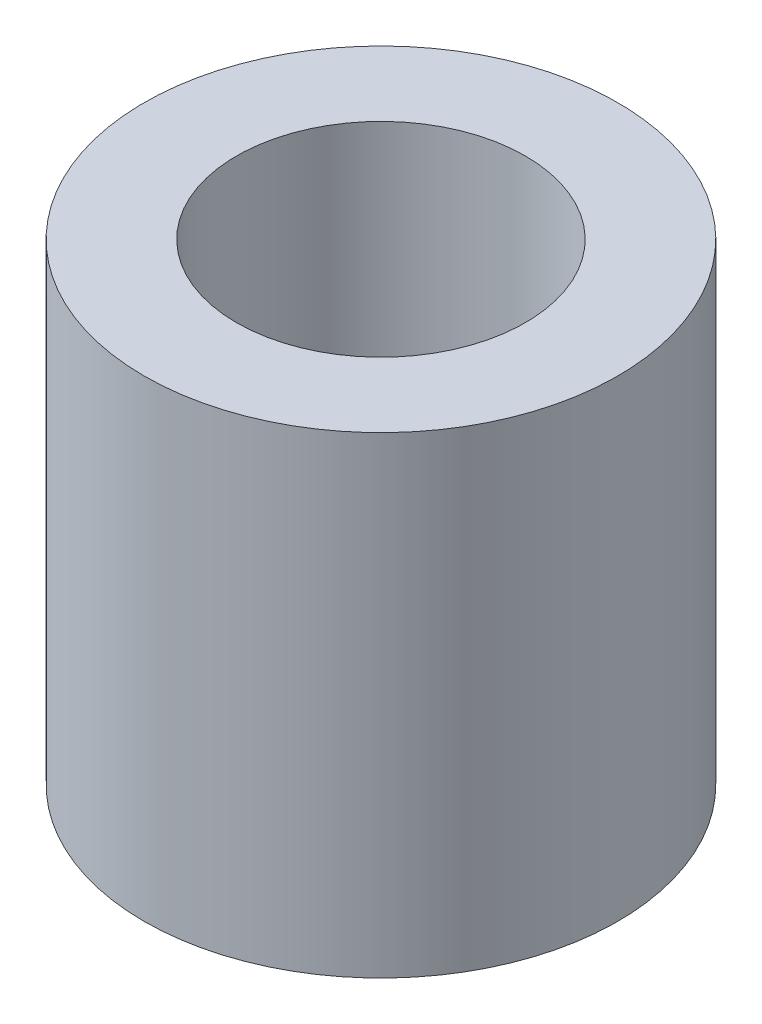
SolidWorks part; units mm, degrees
ref_plane "Plan de face" through (0, 0, 0) normal (0, 0, 1) x (1, 0, 0)
ref_plane "Plan de dessus" through (0, 0, 0) normal (0, 1, 0) x (1, 0, 0)
ref_plane "Plan de droite" through (0, 0, 0) normal (1, 0, 0) x (0, 0, -1)
sketch "Sketch1" plane through (0, 0, 0) normal (0, 1, 0) x (1, 0, 0)
  circle A0 centre (0, 0) radius 6.1
  circle A1 centre (0, 0) radius 10
  dimension "D1" = 12.2
  dimension "D2" = 20
extrude "Boss-Extrude1" add sketch "Sketch1" along normal mid plane 19.95
